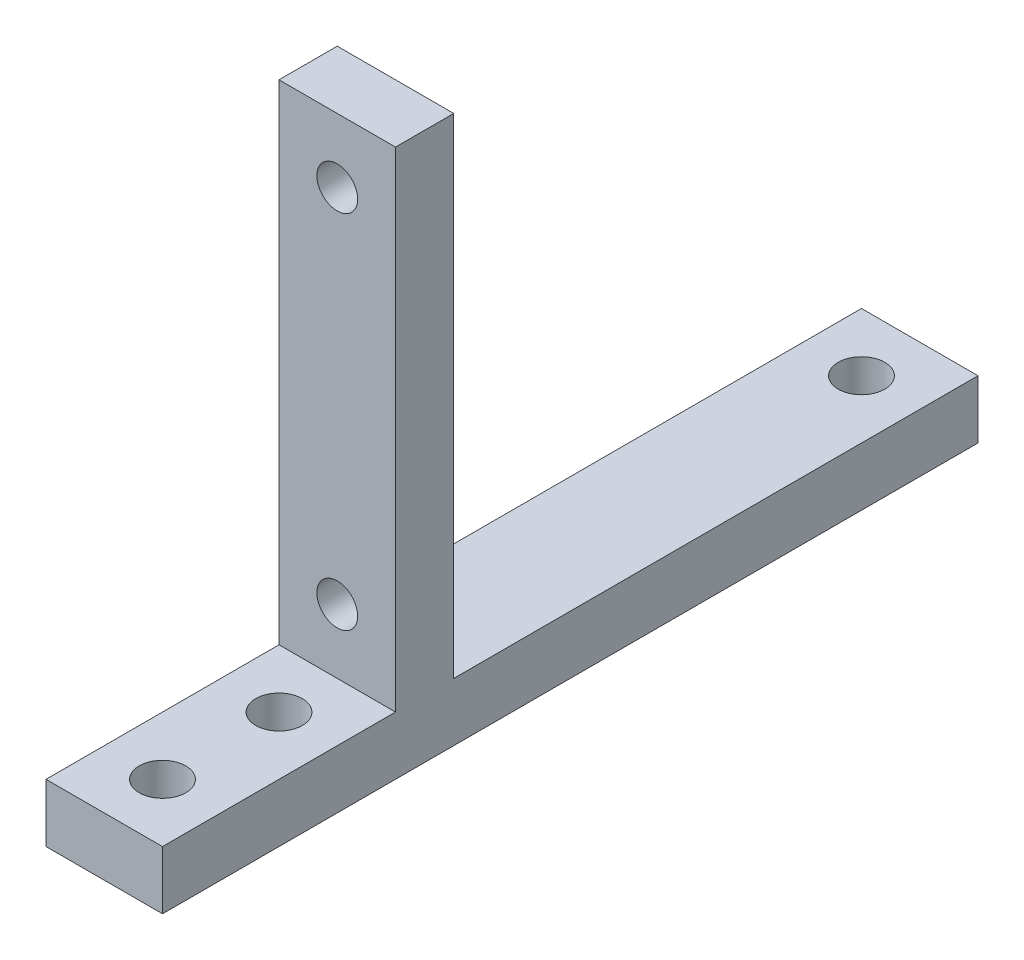
SolidWorks part; units mm, degrees
material "ABS"
ref_plane "Plano frontal" through (0, 0, 0) normal (0, 0, 1) x (1, 0, 0)
ref_plane "Plano superior" through (0, 0, 0) normal (0, 1, 0) x (1, 0, 0)
ref_plane "Plano direito" through (0, 0, 0) normal (1, 0, 0) x (0, 0, -1)
sketch "Esboço1" plane through (0, 0, 0) normal (0, 0, 1) x (1, 0, 0)
  line L0 (5, -21) -> (5, 21)
  line L1 (-5, 21) -> (5, 21)
  line L2 (-5, 21) -> (-5, -21)
  line L3 (-5, -21) -> (5, -21)
  line L11 (0, 15.5) -> (0, -15.5) construction
  circle A1 centre (0, 15.5) radius 1.75
  circle A4 centre (0, -15.5) radius 1.75
  point P0 (0, 0)
  point P1 (0, 21)
  point P4 (0, 0)
  point P7 (5, 0)
  dimension "D2" = 31
  dimension "D4" = 10
  dimension "D1" = 3.5
  dimension "D3" = 42
extrude "Ressalto-extrusão1" add sketch "Esboço1" along normal blind 5
sketch "Esboço2" plane through (0, -21, 0) normal (0, -1, 0) x (1, 0, 0)
  line L0 (-5, 5) -> (-5, 0) construction
  line L1 (-5, 25) -> (5, 25)
  line L2 (-5, 25) -> (-5, -45)
  line L3 (-5, -45) -> (5, -45)
  line L4 (5, 25) -> (5, -45)
  line L5 (5, 5) -> (5, 0) construction
  line L6 (0, 20) -> (0, -40) construction
  line L7 (-5, 5) -> (5, 5) construction
  circle A0 centre (0, 20) radius 2
  circle A1 centre (0, -40) radius 2
  circle A2 centre (0, 10) radius 2
  point P15 (0, 25)
  dimension "D4" = 10
  dimension "D5" = 4
  dimension "D1" = 60
  dimension "D2" = 5
  dimension "D3" = 5
  dimension "D6" = 5
extrude "Ressalto-extrusão2" add sketch "Esboço2" along normal blind 5
